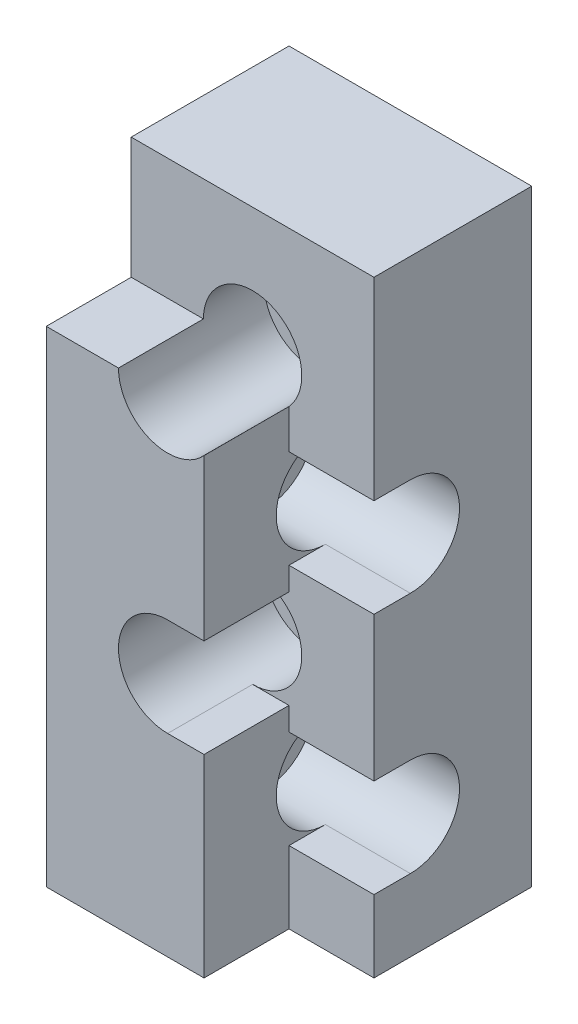
SolidWorks part; units mm, degrees
ref_plane "Alzado" through (0, 0, 0) normal (0, 0, 1) x (1, 0, 0)
ref_plane "Planta" through (0, 0, 0) normal (0, 1, 0) x (1, 0, 0)
ref_plane "Vista lateral" through (0, 0, 0) normal (1, 0, 0) x (0, 0, -1)
sketch "Croquis1" plane through (0, 0, 0) normal (0, 1, 0) x (1, 0, 0)
  line L0 (0, 0) -> (0, 20)
  line L1 (0, 20) -> (20, 20)
  line L2 (20, 20) -> (20, 7)
  line L3 (20, 7) -> (13, 7)
  line L5 (13, 7) -> (13, 0)
  line L6 (13, 0) -> (0, 0)
  point P3 (0, 0)
  dimension "D1" = 20
  dimension "D2" = 20
  dimension "D3" = 13
extrude "Saliente-Extruir1" add sketch "Croquis1" along normal blind 40
sketch "Croquis2" plane through (0, 40, 0) normal (0, 1, 0) x (1, 0, 0)
  line L1 (20, 7) -> (0, 7)
  line L2 (20, 7) -> (20, 20)
  line L3 (20, 20) -> (0, 20)
  line L4 (0, 7) -> (0, 20)
extrude "Saliente-Extruir2" add sketch "Croquis2" along normal blind 10
sketch "Croquis3" plane through (13, 0, 0) normal (1, 0, 0) x (0, 0, -1)
  line L0 (0, 0) -> (20, 0) construction
  line L1 (10, 0) -> (10, 40) construction
  line L2 (0, 40) -> (7, 40) construction
  line L3 (0, 40) -> (0, 0) construction
  circle A0 centre (10, 30) radius 2.125
  circle A1 centre (10, 10) radius 2.125
  dimension "D2" = 4.25
  dimension "D3" = 4.25
  dimension "D1" = 10
  dimension "D4" = 10
  dimension "D5" = 20
extrude "Cortar-Extruir1" cut sketch "Croquis3" against normal through all
sketch "Croquis4" plane through (13, 0, 0) normal (1, 0, 0) x (0, 0, -1)
  circle A0 centre (10, 30) radius 4.05
  circle A1 centre (10, 10) radius 4.05
  dimension "D1" = 8.1
  dimension "D2" = 8.1
extrude "Cortar-Extruir2" cut sketch "Croquis4" against normal blind 5 and the other way through all
sketch "Croquis5" plane through (0, 0, -7) normal (0, 0, 1) x (1, 0, 0)
  line L0 (20, 20) -> (0, 20) construction
  line L1 (20, 27.2792) -> (20, 12.7208) construction
  line L2 (0, 40) -> (0, 0) construction
  circle A0 centre (10, 20) radius 2.125
  dimension "D1" = 4.25
extrude "Cortar-Extruir3" cut sketch "Croquis5" against normal through all both and the other way through all
sketch "Croquis6" plane through (0, 0, 0) normal (0, 0, 1) x (1, 0, 0)
  circle A0 centre (10, 20) radius 4.05
  dimension "D1" = 8.1
extrude "Cortar-Extruir4" cut sketch "Croquis6" against normal blind 5 and the other way through all from surface at -7 starting at face at (16.5, 20, -7)
sketch "Croquis7" plane through (0, 0, 0) normal (0, 0, 1) x (1, 0, 0)
  line L0 (10, 24.05) -> (18, 24.05)
  line L1 (18, 24.05) -> (18, 15.95)
  line L2 (18, 15.95) -> (10, 15.95)
  line L3 (0, 40) -> (0, 0) construction
  circle A0 centre (10, 20) radius 4.05 construction
  arc A1 (13, 22.7208) -> (13, 17.2792) centre (10, 20) ccw construction
  arc A2 (10, 15.95) -> (10, 24.05) centre (10, 20) ccw
  point P11 (10, 15.95)
  point P12 (10, 15.95)
  point P13 (0, 0)
  point P14 (0, 0)
  dimension "D1" = 18
  dimension "D2" = 8.1
extrude "Cortar-Extruir5" cut sketch "Croquis7" against normal up to vertex (7 mm away)
sketch "Croquis8" plane through (20, 0, 0) normal (1, 0, 0) x (0, 0, -1)
  line L0 (10, 34.05) -> (0, 34.05)
  line L1 (0, 34.05) -> (0, 25.95)
  line L2 (0, 25.95) -> (10, 25.95)
  line L3 (10, 14.05) -> (0, 14.05)
  line L4 (0, 15.95) -> (0, 0) construction
  line L5 (0, 14.05) -> (0, 5.95)
  line L6 (0, 5.95) -> (10, 5.95)
  line L7 (0, 40) -> (0, 24.05) construction
  circle A0 centre (10, 30) radius 4.05 construction
  arc A1 (7, 27.2792) -> (7, 32.7208) centre (10, 30) ccw construction
  circle A2 centre (10, 10) radius 4.05 construction
  arc A3 (7, 7.2792) -> (7, 12.7208) centre (10, 10) ccw construction
  arc A4 (10, 14.05) -> (10, 5.95) centre (10, 10) ccw
  arc A5 (10, 34.05) -> (10, 25.95) centre (10, 30) ccw
  point P18 (0, 0)
  point P23 (0, 0)
  point P24 (0, 0)
  point P25 (10, 25.95)
  point P26 (0, 0)
  point P27 (0, 0)
  point P28 (0, 0)
  dimension "D1" = 8.1
  dimension "D2" = 8.1
extrude "Cortar-Extruir6" cut sketch "Croquis8" against normal up to vertex (7 mm away) up to point (13, 40, 0)
sketch "Croquis9" plane through (0, 0, 0) normal (0, 0, 1) x (1, 0, 0)
  line L0 (10, 40) -> (10, 20) construction
  circle A0 centre (10, 40) radius 2.125
  dimension "D1" = 4.25
  dimension "D2" = 20
extrude "Cortar-Extruir7" cut sketch "Croquis9" against normal through all
sketch "Croquis10" plane through (0, 0, 0) normal (0, 0, 1) x (1, 0, 0)
  circle A0 centre (10, 40) radius 4.05
  dimension "D1" = 8.1
extrude "Cortar-Extruir8" cut sketch "Croquis10" against normal blind 5 and the other way through all from surface at -7 starting at face at (10.75, 41.2781, -7)
